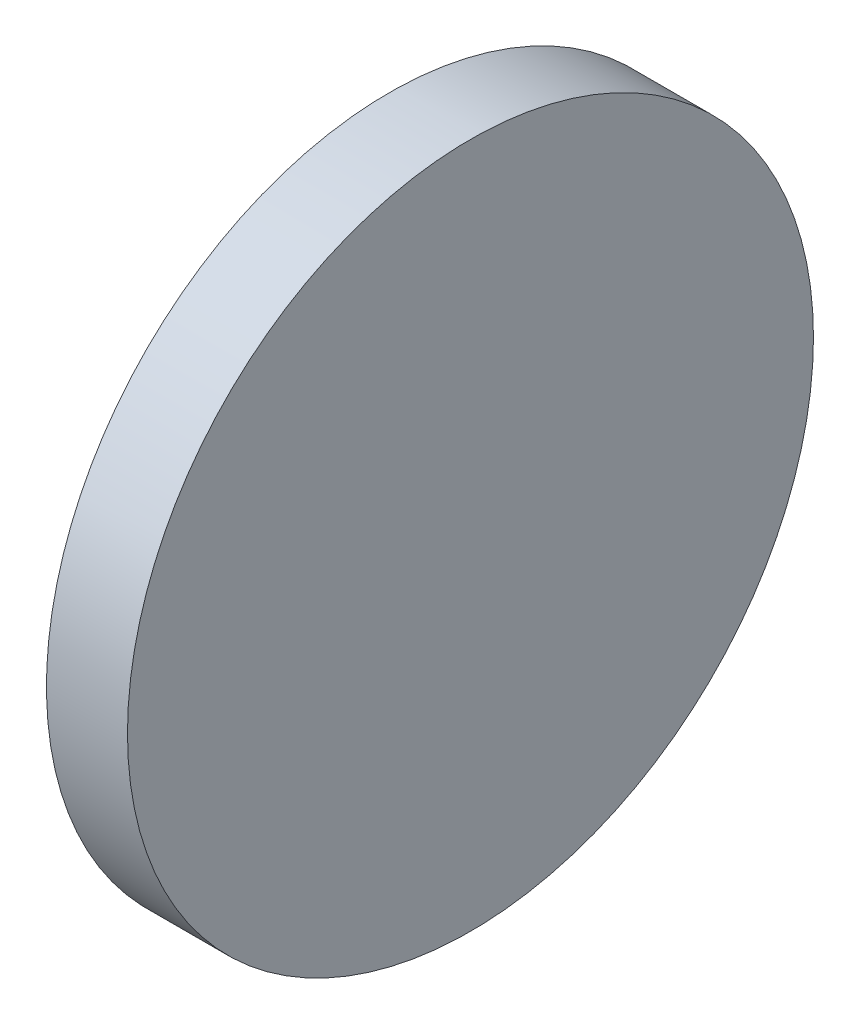
SolidWorks part; units mm, degrees
material "Silicon Dioxide"
ref_plane "Front Plane" through (0, 0, 0) normal (0, 0, 1) x (1, 0, 0)
ref_plane "Top Plane" through (0, 0, 0) normal (0, 1, 0) x (1, 0, 0)
ref_plane "Right Plane" through (0, 0, 0) normal (1, 0, 0) x (0, 0, -1)
sketch "Sketch2" plane through (0, 0, 0) normal (0, 0, 1) x (1, 0, 0)
  line L0 (0, 0) -> (0, 12.7)
  line L2 (0, 0) -> (-3, 0)
  line L3 (0, 12.7) -> (23.7239, 12.7) construction
  line L4 (23.7239, 12.7) -> (-15.601, 12.7) construction
  line L5 (0, 12.7) -> (-4.3, 12.7)
  arc A0 (-3, 0) -> (-4.3, 12.7) centre (58.3846, 12.7) cw
  dimension "D1" = 12.7
  dimension "D2" = 4.3
  dimension "D3" = 3
revolve "Revolve3" add sketch "Sketch2" angle 360 about L4
